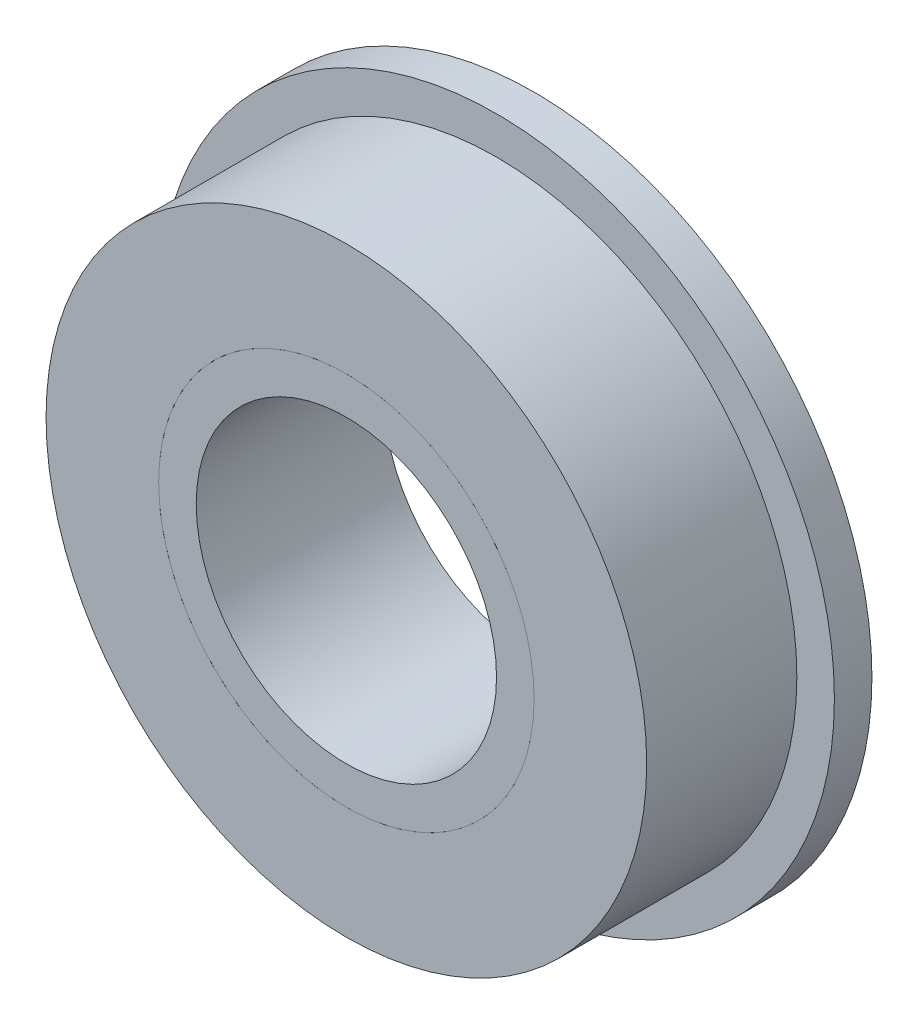
SolidWorks part; units mm, degrees
ref_plane "Спереди" through (0, 0, 0) normal (0, 0, 1) x (1, 0, 0)
ref_plane "Сверху" through (0, 0, 0) normal (0, 1, 0) x (1, 0, 0)
ref_plane "Справа" through (0, 0, 0) normal (1, 0, 0) x (0, 0, -1)
sketch "Эскиз1" plane through (0, 0, 0) normal (0, 0, 1) x (1, 0, 0)
  circle A0 centre (0, 0) radius 9
  circle A1 centre (0, 0) radius 5
  dimension "D1" = 18
  dimension "D2" = 10
extrude "Бобышка-Вытянуть1" add sketch "Эскиз1" along normal blind 5
sketch "Эскиз2" plane through (0, 0, 5) normal (0, 0, 1) x (1, 0, 0)
  circle A0 centre (0, 0) radius 8
  circle A1 centre (0, 0) radius 9
  circle A4 centre (0, 0) radius 9 construction
  dimension "D1" = 16
extrude "Вырез-Вытянуть1" cut sketch "Эскиз2" against normal offset from surface (4 mm away) 1 up to face at (9, 0, 0)
sketch "Эскиз3" plane through (0, 0, 0) normal (0, 0, -1) x (-1, 0, 0)
  circle A0 centre (0, 0) radius 4
  circle A1 centre (0, 0) radius 5
  circle A2 centre (0, 0) radius 5 construction
  dimension "D1" = 8
extrude "Бобышка-Вытянуть2" add sketch "Эскиз3" against normal up to surface (5 mm away) separate body up to face at (5, 0, 5)
